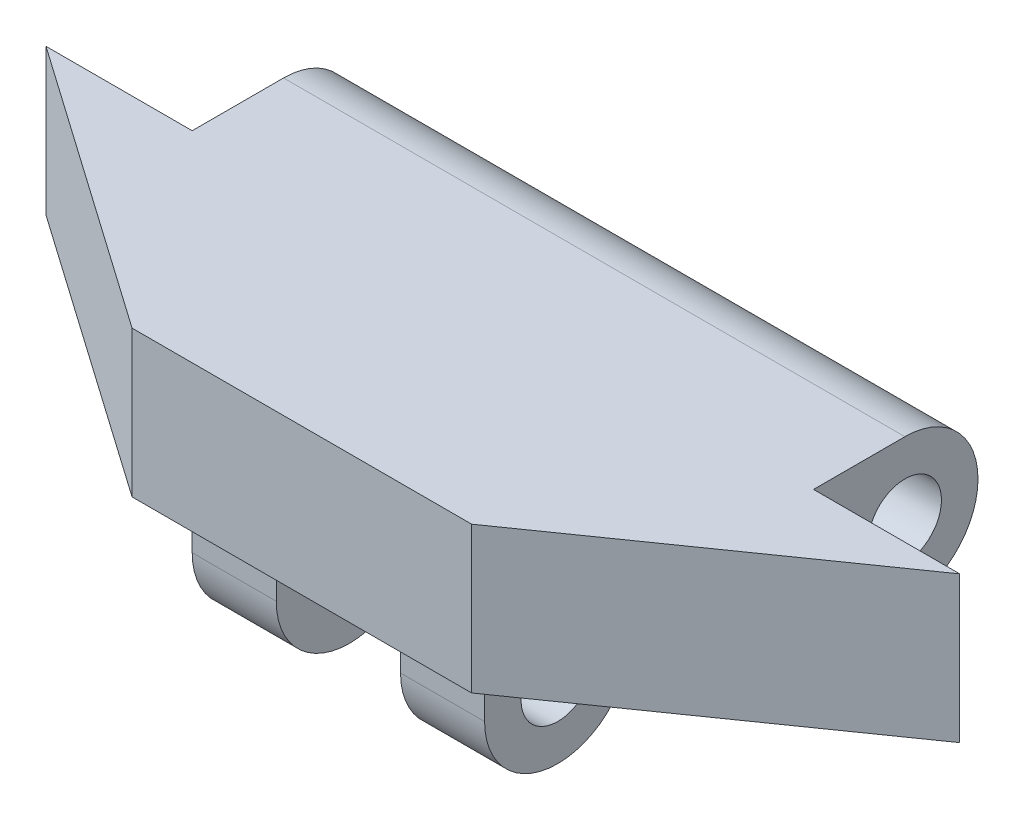
SolidWorks part; units mm, degrees
ref_plane "Front Plane" through (0, 0, 0) normal (0, 0, 1) x (1, 0, 0)
ref_plane "Top Plane" through (0, 0, 0) normal (0, 1, 0) x (1, 0, 0)
ref_plane "Right Plane" through (0, 0, 0) normal (1, 0, 0) x (0, 0, -1)
sketch "Sketch1" plane through (0, 0, 0) normal (0, 1, 0) x (1, 0, 0)
  line L0 (0, 0) -> (7.8548, -5.5)
  line L1 (0, 0) -> (25, 0)
  line L3 (7.8548, -5.5) -> (17.1452, -5.5)
  line L5 (12.5, 0) -> (12.5, -5.5) construction
  line L6 (25, 0) -> (17.1452, -5.5)
  dimension "D1" = 25
  dimension "D2" = 5.5
  dimension "D3" = 35
extrude "Boss-Extrude1" add sketch "Sketch1" along normal blind 4
sketch "Sketch2" plane through (0, 0, 0) normal (1, 0, 0) x (0, 0, -1)
  line L1 (0, 0) -> (2.5, 0)
  line L2 (0, 0) -> (0, 4)
  line L3 (0, 4) -> (2.5, 4)
  arc A0 (2.5, 0) -> (2.5, 4) centre (2.5, 2) ccw
  circle A1 centre (2.5, 2) radius 1
  dimension "D3" = 2
  dimension "D1" = 2.5
extrude "Boss-Extrude2" add sketch "Sketch2" along normal blind 17 from offset 4
sketch "Sketch3" plane through (0, 0, 0) normal (1, 0, 0) x (0, 0, -1)
  line L0 (-5.5, 4) -> (-5.5, 0) construction
  line L1 (-4.5, 0) -> (-0.5, 0)
  line L2 (-4.5, 0) -> (-4.5, -1.5)
  line L4 (-0.5, 0) -> (-0.5, -1.5)
  line L5 (-5.5, 0) -> (0, 0) construction
  arc A0 (-4.5, -1.5) -> (-0.5, -1.5) centre (-2.5, -1.5) ccw
  circle A1 centre (-2.5, -1.5) radius 1
  circle A2 centre (2.5, 2) radius 1 construction
  dimension "D2" = 2
  dimension "D3" = 2
  dimension "D1" = 1.5
  dimension "D4" = 1
  dimension "D5" = 5
extrude "Boss-Extrude3" add sketch "Sketch3" along normal blind 4 and the other way blind 4 from offset 12.5
sketch "Sketch4" plane through (0, 0, 5.5) normal (0, 0, 1) x (1, 0, 0)
  line L0 (8.5, -3.5) -> (16.5, -3.5) construction
  line L1 (14.2, 0) -> (10.8, 0)
  line L2 (14.2, 0) -> (14.2, -3.5)
  line L3 (14.2, -3.5) -> (10.8, -3.5)
  line L4 (10.8, 0) -> (10.8, -3.5)
  line L5 (12.5, 4) -> (12.5, -3.5) construction
  line L7 (7.8548, 4) -> (17.1452, 4) construction
  line L8 (7.8548, 0) -> (17.1452, 0) construction
  point P10 (12.5, 0)
  dimension "D1" = 3.4
extrude "Cut-Extrude1" cut sketch "Sketch4" against normal up to next
sketch "Sketch5" plane through (14.2, 0, 0) normal (-1, 0, 0) x (0, 0, 1)
  line L0 (4.5, 0) -> (0.5, 0)
  arc A0 (4.5, 0) -> (0.5, 0) centre (2.5, -1.5) ccw
extrude "Cut-Extrude2" cut sketch "Sketch5" along normal up to surface (3.4 mm away) up to face at (10.8, -1.5, 3.5)
